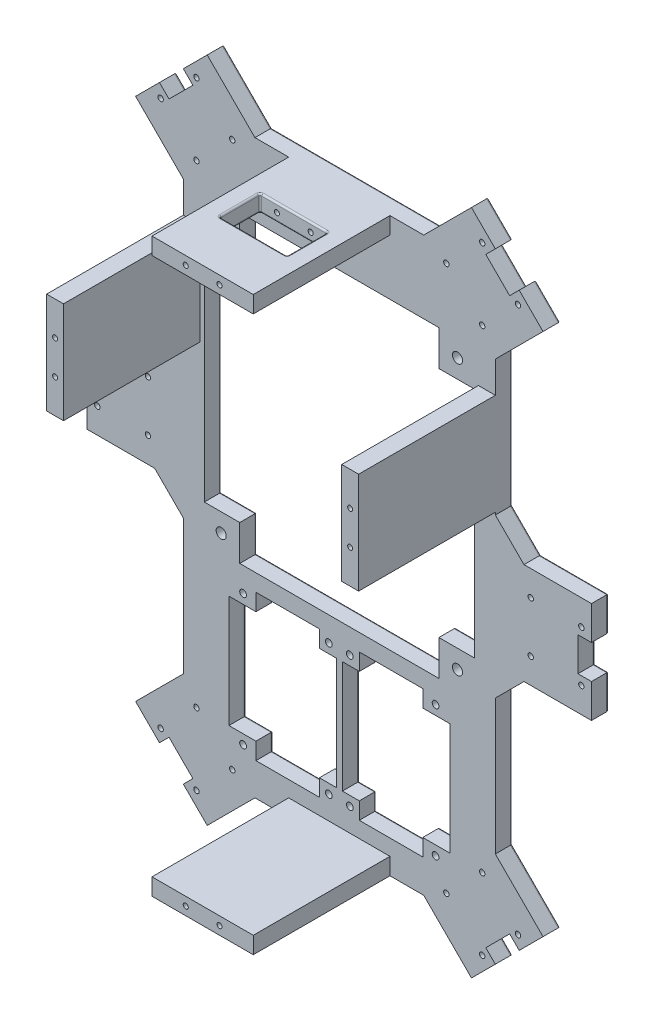
SolidWorks part; units mm, degrees
ref_plane "Płaszczyzna przednia" through (0, 0, 0) normal (0, 0, 1) x (1, 0, 0)
ref_plane "Płaszczyzna górna" through (0, 0, 0) normal (0, 1, 0) x (1, 0, 0)
ref_plane "Płaszczyzna prawa" through (0, 0, 0) normal (1, 0, 0) x (0, 0, -1)
sketch "Szkic1" plane through (0, 0, 0) normal (0, 0, 1) x (1, 0, 0)
  line L0 (0, 0) -> (-50, 0)
  line L1 (-50, 0) -> (-64.1421, 14.1421)
  line L2 (-64.1421, 14.1421) -> (-71.2132, 7.0711)
  line L3 (-71.2132, 7.0711) -> (-68.3848, 4.2426)
  line L4 (-68.3848, 4.2426) -> (-75.4558, -2.8284)
  line L5 (-75.4558, -2.8284) -> (-78.2843, 0)
  line L6 (-78.2843, 0) -> (-85.3553, -7.0711)
  line L7 (-85.3553, -7.0711) -> (-71.2132, -21.2132)
  line L8 (-71.2132, -21.2132) -> (-71.2132, -61.2132)
  line L9 (0, 0) -> (14.1421, 14.1421)
  line L10 (14.1421, 14.1421) -> (21.2132, 7.0711)
  line L11 (21.2132, 7.0711) -> (18.3848, 4.2426)
  line L12 (18.3848, 4.2426) -> (25.4558, -2.8284)
  line L13 (25.4558, -2.8284) -> (28.2843, 0)
  line L14 (28.2843, 0) -> (35.3553, -7.0711)
  line L15 (35.3553, -7.0711) -> (21.2132, -21.2132)
  line L16 (21.2132, -21.2132) -> (21.2132, -61.2132)
  line L17 (-71.2132, -61.2132) -> (-79.6985, -69.6985)
  line L18 (-79.6985, -69.6985) -> (-99.6985, -69.6985)
  line L19 (-99.6985, -69.6985) -> (-99.6985, -79.6985)
  line L20 (-99.6985, -79.6985) -> (-95.6985, -79.6985)
  line L21 (-95.6985, -79.6985) -> (-95.6985, -89.6985)
  line L22 (-95.6985, -89.6985) -> (-99.6985, -89.6985)
  line L23 (-99.6985, -89.6985) -> (-99.6985, -99.6985)
  line L24 (-99.6985, -99.6985) -> (-79.6985, -99.6985)
  line L25 (21.2132, -61.2132) -> (29.6985, -69.6985)
  line L26 (29.6985, -69.6985) -> (49.6985, -69.6985)
  line L27 (49.6985, -69.6985) -> (49.6985, -79.6985)
  line L28 (49.6985, -79.6985) -> (45.6985, -79.6985)
  line L29 (45.6985, -79.6985) -> (45.6985, -89.6985)
  line L30 (45.6985, -89.6985) -> (49.6985, -89.6985)
  line L31 (49.6985, -89.6985) -> (49.6985, -99.6985)
  line L32 (49.6985, -99.6985) -> (29.6985, -99.6985)
  line L33 (29.6985, -99.6985) -> (21.2132, -108.1838)
  line L34 (-79.6985, -99.6985) -> (-71.2132, -108.1838)
  line L35 (-71.2132, -108.1838) -> (-71.2132, -148.1838)
  line L36 (21.2132, -108.1838) -> (21.2132, -148.1838)
  line L37 (-71.2132, -148.1838) -> (-85.3553, -162.3259)
  line L38 (-85.3553, -162.3259) -> (-78.2843, -169.397)
  line L39 (-78.2843, -169.397) -> (-75.4558, -166.5685)
  line L40 (-75.4558, -166.5685) -> (-68.3848, -173.6396)
  line L41 (-68.3848, -173.6396) -> (-71.2132, -176.468)
  line L42 (-71.2132, -176.468) -> (-64.1421, -183.5391)
  line L43 (-64.1421, -183.5391) -> (-50, -169.397)
  line L44 (21.2132, -148.1838) -> (35.3553, -162.3259)
  line L45 (35.3553, -162.3259) -> (28.2843, -169.397)
  line L46 (28.2843, -169.397) -> (25.4558, -166.5685)
  line L47 (25.4558, -166.5685) -> (18.3848, -173.6396)
  line L48 (18.3848, -173.6396) -> (21.2132, -176.468)
  line L49 (21.2132, -176.468) -> (14.1421, -183.5391)
  line L50 (14.1421, -183.5391) -> (0, -169.397)
  line L51 (-50, -169.397) -> (0, -169.397)
  dimension "D1" = 225
  dimension "D2" = 225
  dimension "D3" = 20
  dimension "D4" = 20
  dimension "D5" = 10
  dimension "D6" = 4
  dimension "D7" = 50
  dimension "D8" = 10
  dimension "D9" = 10
  dimension "D10" = 20
  dimension "D11" = 4
  dimension "D12" = 10
  dimension "D13" = 4
  dimension "D14" = 10
  dimension "D15" = 4
  dimension "D16" = 10
  dimension "D17" = 20
  dimension "D18" = 225
  dimension "D19" = 40
  dimension "D20" = 12
  dimension "D21" = 20
  dimension "D22" = 10
  dimension "D23" = 4
  dimension "D24" = 10
  dimension "D25" = 4
  dimension "D26" = 10
  dimension "D27" = 20
  dimension "D29" = 12
  dimension "D30" = 20
  dimension "D31" = 10
  dimension "D32" = 4
  dimension "D33" = 10
  dimension "D34" = 4
  dimension "D35" = 10
  dimension "D36" = 20
  dimension "D37" = 12
  dimension "D38" = 12
  dimension "D39" = 40
  dimension "D40" = 40
  dimension "D41" = 20
  dimension "D42" = 10
  dimension "D43" = 4
  dimension "D44" = 10
  dimension "D45" = 4
  dimension "D46" = 10
  dimension "D47" = 20
  dimension "D48" = 20
  dimension "D49" = 10
  dimension "2" = 4
  dimension "D51" = 10
  dimension "D52" = 4
  dimension "D53" = 10
  dimension "D54" = 20
  dimension "D55" = 135
  dimension "D56" = 90
  dimension "D57" = 270
  dimension "D58" = 225
  dimension "D59" = 225
  dimension "D60" = 135
extrude "Dodanie-wyciągnięcie1" add sketch "Szkic1" along normal blind 5 contours L36 L44 L45 L46 L47 L48 L49 L50 L51 L43 L42 L41 L40 L39 L38 L37 L35 L34 L24 L23 L22 L21 L20 L19 L18 L17 L8 L7 L6 L5 L4 L3 L2 L1 L0 L9 L10 L11 L12 L13 L14 L15 L16 L25 L26 L27 L28 L29 L30 L31 L32 L33
sketch "Szkic3" plane through (0, 0, 0) normal (0, 0, 1) x (1, 0, 0)
  line L0 (49.6985, -69.6985) -> (49.6985, -79.6985) construction
  line L1 (29.6985, -69.6985) -> (49.6985, -69.6985) construction
  line L2 (35.3553, -162.3259) -> (28.2843, -169.397) construction
  line L3 (21.2132, -148.1838) -> (35.3553, -162.3259) construction
  line L4 (21.2132, -176.468) -> (14.1421, -183.5391) construction
  line L5 (14.1421, -183.5391) -> (0, -169.397) construction
  line L6 (-71.2132, -176.468) -> (-64.1421, -183.5391) construction
  line L7 (-85.3553, -162.3259) -> (-78.2843, -169.397) construction
  line L8 (-71.2132, -148.1838) -> (-85.3553, -162.3259) construction
  line L9 (-64.1421, -183.5391) -> (-50, -169.397) construction
  line L10 (35.3553, -7.0711) -> (21.2132, -21.2132) construction
  line L11 (28.2843, 0) -> (35.3553, -7.0711) construction
  line L12 (14.1421, 14.1421) -> (21.2132, 7.0711) construction
  line L13 (0, 0) -> (14.1421, 14.1421) construction
  line L14 (-85.3553, -7.0711) -> (-71.2132, -21.2132) construction
  line L15 (-50, 0) -> (-64.1421, 14.1421) construction
  line L16 (-78.2843, 0) -> (-85.3553, -7.0711) construction
  line L17 (-64.1421, 14.1421) -> (-71.2132, 7.0711) construction
  line L18 (49.6985, -99.6985) -> (29.6985, -99.6985) construction
  line L19 (49.6985, -89.6985) -> (49.6985, -99.6985) construction
  line L20 (-99.6985, -89.6985) -> (-99.6985, -99.6985) construction
  line L21 (-99.6985, -69.6985) -> (-99.6985, -79.6985) construction
  line L22 (-99.6985, -99.6985) -> (-79.6985, -99.6985) construction
  line L23 (-79.6985, -69.6985) -> (-99.6985, -69.6985) construction
  circle A0 centre (31.6985, -77.1985) radius 0.8
  circle A1 centre (46.6985, -77.1985) radius 0.8
  circle A2 centre (31.6985, -92.1985) radius 0.8
  circle A3 centre (46.6985, -92.1985) radius 0.8
  circle A4 centre (-81.6985, -77.1985) radius 0.8
  circle A5 centre (-96.6985, -77.1985) radius 0.8
  circle A6 centre (17.3241, -154.9013) radius 0.8
  circle A7 centre (27.9307, -165.5079) radius 0.8
  circle A8 centre (17.3241, -176.1145) radius 0.8
  circle A9 centre (6.7175, -165.5079) radius 0.8
  circle A10 centre (-67.3241, -154.9013) radius 0.8
  circle A11 centre (-77.9307, -165.5079) radius 0.8
  circle A12 centre (-67.3241, -176.1145) radius 0.8
  circle A13 centre (-56.7175, -165.5079) radius 0.8
  circle A14 centre (17.3241, 6.7175) radius 0.8
  circle A15 centre (27.9307, -3.8891) radius 0.8
  circle A16 centre (6.7175, -3.8891) radius 0.8
  circle A17 centre (17.3241, -14.4957) radius 0.8
  circle A18 centre (-67.3241, 6.7175) radius 0.8
  circle A19 centre (-56.7175, -3.8891) radius 0.8
  circle A20 centre (-77.9307, -3.8891) radius 0.8
  circle A21 centre (-67.3241, -14.4957) radius 0.8
  circle A22 centre (-96.6985, -92.1985) radius 0.8
  circle A23 centre (-81.6985, -92.1985) radius 0.8
  dimension "D1" = 1.6
  dimension "D4" = 1.6
  dimension "D6" = 1.6
  dimension "D7" = 1.6
  dimension "D10" = 1.6
  dimension "D13" = 1.6
  dimension "D16" = 1.6
  dimension "D17" = 1.6
  dimension "D22" = 1.6
  dimension "D23" = 1.6
  dimension "D24" = 1.6
  dimension "D25" = 1.6
  dimension "D34" = 1.6
  dimension "D35" = 1.6
  dimension "D36" = 1.6
  dimension "D37" = 1.6
  dimension "D46" = 1.6
  dimension "D47" = 1.6
  dimension "D48" = 1.6
  dimension "D49" = 1.6
  dimension "D61" = 1.6
  dimension "D62" = 1.6
  dimension "D63" = 1.6
  dimension "D64" = 1.6
  dimension "D2" = 18
  dimension "D3" = 7.5
  dimension "D5" = 15
  dimension "D8" = 15
  dimension "D9" = 15
  dimension "D11" = 18
  dimension "D12" = 7.5
  dimension "D14" = 15
  dimension "D15" = 7.5
  dimension "D18" = 18
  dimension "D19" = 7.5
  dimension "D20" = 7.5
  dimension "D21" = 15
  dimension "D26" = 15
  dimension "D27" = 15
  dimension "D28" = 18
  dimension "D29" = 18
  dimension "D30" = 7.5
  dimension "D31" = 7.5
  dimension "D32" = 7.5
  dimension "D33" = 7.5
  dimension "D38" = 15
  dimension "D39" = 15
  dimension "D40" = 7.5
  dimension "D41" = 7.5
  dimension "D42" = 18
  dimension "D43" = 18
  dimension "D44" = 7.5
  dimension "D45" = 7.5
  dimension "D50" = 7.5
  dimension "D51" = 7.5
  dimension "D52" = 7.5
  dimension "D53" = 7.5
  dimension "D54" = 18
  dimension "D55" = 18
  dimension "D56" = 15
  dimension "D57" = 15
  dimension "D58" = 7.5
  dimension "D59" = 7.5
  dimension "D60" = 18
  dimension "D65" = 18
  dimension "D66" = 18
  dimension "D67" = 15
  dimension "D68" = 15
  dimension "D69" = 7.5
  dimension "D70" = 7.5
  dimension "D71" = 7.5
  dimension "D72" = 7.5
  dimension "D73" = 15
extrude "Wytnij-wyciągnięcie3" cut sketch "Szkic3" against normal blind 4 and the other way blind 16
sketch "Szkic5" plane through (0, 0, 0) normal (0, 0, 1) x (1, 0, 0)
  line L0 (4.4968, -21.5) -> (-54.5032, -21.5)
  line L1 (-54.5032, -21.5) -> (-54.5032, -32)
  line L2 (-54.5032, -32) -> (-65.0032, -32)
  line L3 (-65.0032, -32) -> (-65.0032, -101)
  line L4 (-65.0032, -101) -> (-54.5032, -101)
  line L5 (-54.5032, -101) -> (-54.5032, -111.5)
  line L6 (-54.5032, -111.5) -> (4.4968, -111.5)
  line L7 (4.4968, -111.5) -> (4.4968, -101)
  line L8 (4.4968, -101) -> (14.9968, -101)
  line L9 (14.9968, -101) -> (14.9968, -32)
  line L10 (14.9968, -32) -> (4.4968, -32)
  line L11 (4.4968, -32) -> (4.4968, -21.5)
  line L12 (0, 0) -> (-50, 0) construction
  line L13 (-71.2132, -21.2132) -> (-71.2132, -61.2132) construction
  line L14 (21.2132, -21.2132) -> (21.2132, -61.2132) construction
  line L15 (-71.2132, -21.2132) -> (-71.2132, -61.2132) construction
  circle A0 centre (-60.0032, -26.5) radius 1.5
  circle A1 centre (9.9968, -26.5) radius 1.5
  circle A2 centre (9.9968, -106.5) radius 1.5
  circle A3 centre (-60.0032, -106.5) radius 1.5
  point P14 (-59.7532, -32)
  dimension "D16" = 3
  dimension "D19" = 3
  dimension "D22" = 3
  dimension "D25" = 3
  dimension "D1" = 21.5
  dimension "D2" = 69
  dimension "D3" = 10.5
  dimension "D4" = 10.5
  dimension "D5" = 90
  dimension "D6" = 10.5
  dimension "D7" = 59
  dimension "D8" = 6.21
  dimension "D9" = 10.5
  dimension "D10" = 10.5
  dimension "D11" = 59
  dimension "D12" = 10.5
  dimension "D13" = 10.5
  dimension "D14" = 10.5
  dimension "D15" = 80
  dimension "D17" = 5.5
  dimension "D18" = 5.5
  dimension "D20" = 5.5
  dimension "D21" = 5.5
  dimension "D23" = 5.5
  dimension "D24" = 5.5
  dimension "D26" = 5.5
  dimension "D27" = 5.5
  dimension "D28" = 5
  dimension "D29" = 5
  dimension "D30" = 5
  dimension "D31" = 5
  dimension "D32" = 5
  dimension "D33" = 5
  dimension "D34" = 5
  dimension "D35" = 5
  dimension "D36" = 6.2164
  dimension "D37" = 6.21
  dimension "D38" = 80
  dimension "D39" = 70
  dimension "D40" = 80
  dimension "D41" = 70
  dimension "D42" = 70
extrude "Wytnij-wyciągnięcie4" cut sketch "Szkic5" against normal blind 52 and the other way blind 26
sketch "Szkic6" plane through (0, 0, 5) normal (0, 0, 1) x (1, 0, 0)
  line L0 (-30.9132, -116.497) -> (-49.7132, -116.497)
  line L1 (-49.7132, -116.497) -> (-49.7132, -121.497)
  line L2 (-49.7132, -121.497) -> (-57.7132, -121.497)
  line L3 (-57.7132, -121.497) -> (-57.7132, -154.697)
  line L4 (-57.7132, -154.697) -> (-49.7132, -154.697)
  line L5 (-49.7132, -154.697) -> (-49.7132, -159.697)
  line L6 (-49.7132, -159.697) -> (-30.9132, -159.697)
  line L7 (-30.9132, -159.697) -> (-30.9132, -154.697)
  line L8 (-30.9132, -154.697) -> (-25.9132, -154.697)
  line L9 (-25.9132, -154.697) -> (-25.9132, -121.497)
  line L10 (-25.9132, -121.497) -> (-30.9132, -121.497)
  line L11 (-30.9132, -121.497) -> (-30.9132, -116.497)
  line L12 (-50, -169.397) -> (0, -169.397) construction
  line L13 (-0.2868, -121.497) -> (-0.2868, -116.497)
  line L14 (-71.2132, -108.1838) -> (-71.2132, -148.1838) construction
  line L16 (-19.0868, -116.497) -> (-19.0868, -121.497)
  line L17 (-19.0868, -121.497) -> (-24.0868, -121.497)
  line L18 (-24.0868, -121.497) -> (-24.0868, -154.697)
  line L19 (-24.0868, -154.697) -> (-19.0868, -154.697)
  line L20 (-19.0868, -154.697) -> (-19.0868, -159.697)
  line L21 (-19.0868, -159.697) -> (-0.2868, -159.697)
  line L22 (-0.2868, -159.697) -> (-0.2868, -154.697)
  line L23 (-0.2868, -154.697) -> (7.7132, -154.697)
  line L24 (7.7132, -154.697) -> (7.7132, -121.497)
  line L25 (7.7132, -121.497) -> (-0.2868, -121.497)
  line L26 (-19.0868, -116.497) -> (-0.2868, -116.497)
  line L27 (21.2132, -108.1838) -> (21.2132, -148.1838) construction
  line L28 (4.4968, -111.5) -> (-54.5032, -111.5) construction
  dimension "D1" = 43.2
  dimension "D2" = 9.7
  dimension "D3" = 5
  dimension "D4" = 8
  dimension "D5" = 18.8
  dimension "D6" = 8
  dimension "D7" = 5
  dimension "D8" = 5
  dimension "D9" = 5
  dimension "D10" = 5
  dimension "D11" = 13.5
  dimension "D12" = 33.2
  dimension "D13" = 9.7
  dimension "D14" = 43.2
  dimension "D15" = 5
  dimension "D16" = 33.2
  dimension "D17" = 8
  dimension "D18" = 8
  dimension "D19" = 18.8
  dimension "D20" = 5
  dimension "D21" = 5
  dimension "D22" = 5
  dimension "D23" = 5
  dimension "D24" = 13.5
  dimension "D25" = 1.8264
  dimension "D26" = 4.997
  dimension "D27" = 31.8
  dimension "D28" = 31.8
extrude "Wytnij-wyciągnięcie5" cut sketch "Szkic6" against normal blind 69 and the other way blind 31
sketch "Szkic7" plane through (0, 0, 5) normal (0, 0, 1) x (1, 0, 0)
  line L0 (-49.7132, -121.497) -> (-49.7132, -116.497) construction
  line L1 (-57.7132, -121.497) -> (-49.7132, -121.497) construction
  line L2 (-30.9132, -116.497) -> (-30.9132, -121.497) construction
  line L3 (-30.9132, -121.497) -> (-25.9132, -121.497) construction
  line L4 (-24.0868, -121.497) -> (-19.0868, -121.497) construction
  line L5 (-19.0868, -121.497) -> (-19.0868, -116.497) construction
  line L6 (-0.2868, -121.497) -> (7.7132, -121.497) construction
  line L7 (-0.2868, -116.497) -> (-0.2868, -121.497) construction
  line L8 (7.7132, -154.697) -> (-0.2868, -154.697) construction
  line L9 (-0.2868, -154.697) -> (-0.2868, -159.697) construction
  line L10 (-19.0868, -159.697) -> (-19.0868, -154.697) construction
  line L11 (-19.0868, -154.697) -> (-24.0868, -154.697) construction
  line L12 (-25.9132, -154.697) -> (-30.9132, -154.697) construction
  line L13 (-30.9132, -154.697) -> (-30.9132, -159.697) construction
  line L14 (-49.7132, -159.697) -> (-49.7132, -154.697) construction
  line L15 (-49.7132, -154.697) -> (-57.7132, -154.697) construction
  line L16 (-57.7132, -121.497) -> (-57.7132, -154.697) construction
  line L18 (-49.7132, -159.697) -> (-30.9132, -159.697) construction
  line L19 (-25.9132, -121.497) -> (-25.9132, -154.697) construction
  line L20 (-30.9132, -116.497) -> (-49.7132, -116.497) construction
  line L21 (-19.0868, -116.497) -> (-0.2868, -116.497) construction
  line L22 (-24.0868, -121.497) -> (-24.0868, -154.697) construction
  line L23 (7.7132, -121.497) -> (7.7132, -154.697) construction
  line L24 (-0.2868, -159.697) -> (-19.0868, -159.697) construction
  line L25 (7.7132, -154.697) -> (7.7132, -121.497) construction
  line L26 (-30.9132, -159.697) -> (-49.7132, -159.697) construction
  line L27 (-25.9132, -154.697) -> (-25.9132, -121.497) construction
  circle A0 centre (-53.5132, -118.697) radius 1
  circle A1 centre (-28.1132, -118.697) radius 1
  circle A2 centre (-21.8868, -118.697) radius 1
  circle A3 centre (3.5132, -118.697) radius 1
  circle A4 centre (3.5132, -157.497) radius 1
  circle A5 centre (-21.8868, -157.497) radius 1
  circle A6 centre (-28.1132, -157.497) radius 1
  circle A7 centre (-53.5132, -157.497) radius 1
  dimension "D1" = 2
  dimension "D4" = 2
  dimension "D5" = 2
  dimension "D10" = 2
  dimension "D13" = 2
  dimension "D16" = 2
  dimension "D17" = 2
  dimension "D22" = 2
  dimension "D2" = 3.8
  dimension "D3" = 2.8
  dimension "D6" = 2.8
  dimension "D7" = 2.8
  dimension "D8" = 2.8
  dimension "D9" = 2.8
  dimension "D11" = 2.8
  dimension "D12" = 3.8
  dimension "D14" = 2.8
  dimension "D15" = 3.8
  dimension "D18" = 2.8
  dimension "D19" = 2.8
  dimension "D20" = 2.8
  dimension "D21" = 2.8
  dimension "D23" = 3.8
  dimension "D24" = 2.8
  dimension "D25" = 4.2
  dimension "D26" = 4.2
  dimension "D27" = 2.2
  dimension "D28" = 2.2
  dimension "D29" = 2.2
  dimension "D30" = 2.2
  dimension "D31" = 2.2
  dimension "D32" = 2.2
  dimension "D33" = 4.2
  dimension "D34" = 2.2
  dimension "D35" = 2.2
  dimension "D36" = 2.2
  dimension "D37" = 4.2
  dimension "D38" = 2.2
  dimension "D39" = 2.2
  dimension "D40" = 2.2
extrude "Wytnij-wyciągnięcie6" cut sketch "Szkic7" against normal blind 83 and the other way blind 22
sketch "Szkic8" plane through (0, 0, 0) normal (0, 0, 1) x (1, 0, 0)
  line L0 (-40, 0) -> (-40, -5)
  line L1 (0, 0) -> (-50, 0) construction
  line L2 (-40, -5) -> (-10, -5)
  line L3 (-10, -5) -> (-10, 0)
  line L4 (-10, 0) -> (-40, 0)
  dimension "D1" = 10
  dimension "D2" = 30
  dimension "D3" = 10
  dimension "D4" = 5
extrude "Dodanie-wyciągnięcie2" add sketch "Szkic8" along normal blind 45.5 contours L2 L3 L4 L0
sketch "Szkic10" plane through (0, 0, 5) normal (0, 0, 1) x (1, 0, 0)
  line L0 (-40, -169.397) -> (-40, -164.397)
  line L1 (-50, -169.397) -> (0, -169.397) construction
  line L2 (-40, -164.397) -> (-10, -164.397)
  line L3 (-10, -164.397) -> (-10, -169.397)
  line L4 (-10, -169.397) -> (-40, -169.397)
  dimension "D1" = 30
  dimension "D2" = 5
  dimension "D3" = 10
  dimension "D4" = 10
extrude "Dodanie-wyciągnięcie3" add sketch "Szkic10" along normal blind 40.5
sketch "Szkic11" plane through (0, 0, 45.5) normal (0, 0, 1) x (1, 0, 0)
  line L0 (-10, 0) -> (-40, 0) construction
  line L2 (-40, -5) -> (-40, 0) construction
  line L3 (-10, -5) -> (-10, 0) construction
  circle A0 centre (-30, -2.5) radius 0.75
  circle A1 centre (-20, -2.5) radius 0.75
  dimension "D1" = 1.5
  dimension "D2" = 1.5
  dimension "D3" = 2.5
  dimension "D4" = 2.5
  dimension "D5" = 10
  dimension "D6" = 10
  dimension "D7" = 10
sketch "Szkic12" plane through (0, 0, 45.5) normal (0, 0, 1) x (1, 0, 0)
  line L0 (-10, -164.397) -> (-40, -164.397) construction
  line L1 (-10, -164.397) -> (-40, -164.397) construction
  line L3 (-40, -164.397) -> (-40, -169.397) construction
  line L4 (-10, -169.397) -> (-10, -164.397) construction
  circle A0 centre (-30, -166.897) radius 0.75
  circle A1 centre (-20, -166.897) radius 0.75
  dimension "D1" = 1.5
  dimension "D2" = 1.5
  dimension "D3" = 2.5
  dimension "D4" = 2.5
  dimension "D5" = 10
  dimension "D6" = 10
  dimension "D7" = 10
extrude "Wytnij-wyciągnięcie7" cut sketch "Szkic11" against normal blind 158 and the other way blind 112
extrude "Wytnij-wyciągnięcie8" cut sketch "Szkic12" against normal blind 402 and the other way blind 220
sketch "Szkic13" plane through (0, 0, 5) normal (0, 0, 1) x (1, 0, 0)
  line L0 (-71.2132, -30.5) -> (-66.2132, -30.5)
  line L1 (-71.2132, -21.2132) -> (-71.2132, -61.2132) construction
  line L2 (-66.2132, -30.5) -> (-66.2132, -60.5)
  line L3 (-66.2132, -60.5) -> (-71.2132, -60.5)
  line L4 (-71.2132, -60.5) -> (-71.2132, -30.5)
  line L5 (-65.0032, -32) -> (-54.5032, -32) construction
  line L6 (21.2132, -30.5) -> (16.2132, -30.5)
  line L7 (21.2132, -21.2132) -> (21.2132, -61.2132) construction
  line L8 (16.2132, -30.5) -> (16.2132, -60.5)
  line L9 (16.2132, -60.5) -> (21.2132, -60.5)
  line L10 (21.2132, -60.5) -> (21.2132, -30.5)
  line L11 (4.4968, -32) -> (14.9968, -32) construction
  dimension "D1" = 5
  dimension "D2" = 30
  dimension "D3" = 1.5
  dimension "D4" = 5
  dimension "D5" = 1.5
  dimension "D6" = 30
  dimension "D7" = 5
extrude "Dodanie-wyciągnięcie4" add sketch "Szkic13" along normal blind 40.5
sketch "Szkic14" plane through (0, 0, 0) normal (0, 0, 1) x (1, 0, 0)
  line L0 (-66.2132, -60.5) -> (-66.2132, -30.5) construction
  line L3 (16.2132, -30.5) -> (16.2132, -60.5) construction
  line L4 (16.2132, -30.5) -> (16.2132, -60.5) construction
  line L5 (0, 0) -> (-50, 0) construction
  circle A0 centre (-68.7132, -40.5) radius 0.75
  circle A1 centre (-68.7132, -50.5) radius 0.75
  circle A2 centre (18.7132, -40.5) radius 0.75
  circle A3 centre (18.7132, -50.5) radius 0.75
  dimension "D1" = 1.5
  dimension "D2" = 1.5
  dimension "D3" = 1.5
  dimension "D4" = 1.5
  dimension "D5" = 2.5
  dimension "D6" = 40.5
  dimension "D7" = 50.5
  dimension "D8" = 2.5
  dimension "D9" = 40.5
  dimension "D10" = 50.5
  dimension "D11" = 2.5
  dimension "D12" = 2.5
extrude "Wytnij-wyciągnięcie9" cut sketch "Szkic14" against normal blind 85 and the other way blind 48
fillet "Zaokrąglenie1" radius 0.5 132 edges at (-95.8985, -77.1985, 0) (-80.8985, -77.1985, 0) (-95.8985, -92.1985, 0) (-66.5241, -176.1145, 0) (-80.8985, -92.1985, 0) (-27.1132, -118.697, 0) (-20.8868, -118.697, 0) (4.5132, -118.697, 0) (4.5132, -157.497, 0) (-20.8868, -157.497, 0) (-27.1132, -157.497, 0) (-52.5132, -157.497, 0) (-52.5132, -118.697, 0) (-0.2868, -118.997, 0) (3.7132, -121.497, 0) (7.7132, -138.097, 0) (3.7132, -154.697, 0) (-0.2868, -157.197, 0) (-9.6868, -159.697, 0) (-19.0868, -157.197, 0) (-21.5868, -154.697, 0) (-24.0868, -138.097, 0) (-21.5868, -121.497, 0) (-19.0868, -118.997, 0) (-9.6868, -116.497, 0) (32.4985, -77.1985, 0) (-55.9175, -3.8891, 0) (-77.1307, -3.8891, 0) (-66.5241, -14.4957, 0) (-66.5241, -154.9013, 0) (7.5175, -165.5079, 0) (28.7307, -165.5079, 0) (18.1241, -154.9013, 0) (47.4985, -77.1985, 0) (32.4985, -92.1985, 0) (47.4985, -92.1985, 0) (18.1241, -176.1145, 0) (28.7307, -3.8891, 0) (7.5175, -3.8891, 0) (18.1241, -14.4957, 0) (-66.5241, 6.7175, 0) (18.1241, 6.7175, 0) (-55.9175, -165.5079, 0) (-77.1307, -165.5079, 0) (9.7468, -32, 0) (14.9968, -66.5, 0) (9.7468, -101, 0) (4.4968, -106.25, 0) (-25.0032, -111.5, 0) (-54.5032, -106.25, 0) (-59.7532, -101, 0) (-65.0032, -66.5, 0) (-59.7532, -32, 0) (-54.5032, -26.75, 0) (-25.0032, -21.5, 0) (4.4968, -26.75, 0) (-58.5032, -26.5, 0) (11.4968, -26.5, 0) (11.4968, -106.5, 0) (-58.5032, -106.5, 0) (-28.4132, -121.497, 0) (-25.9132, -138.097, 0) (-28.4132, -154.697, 0) (-30.9132, -157.197, 0) (-40.3132, -159.697, 0) (-49.7132, -157.197, 0) (-53.7132, -154.697, 0) (-57.7132, -138.097, 0) (-53.7132, -121.497, 0) (-49.7132, -118.997, 0) (-40.3132, -116.497, 0) (-30.9132, -118.997, 0) (-67.6777, 10.6066, 0) (-69.799, 5.6569, 0) (-71.9203, 0.7071, 0) (-76.8701, -1.4142, 0) (-81.8198, -3.5355, 0) (-78.2843, -14.1421, 0) (-71.2132, -41.2132, 0) (-75.4558, -65.4558, 0) (-89.6985, -69.6985, 0) (-99.6985, -74.6985, 0) (-97.6985, -79.6985, 0) (-95.6985, -84.6985, 0) (-97.6985, -89.6985, 0) (-99.6985, -94.6985, 0) (-89.6985, -99.6985, 0) (-75.4558, -103.9411, 0) (-71.2132, -128.1838, 0) (-78.2843, -155.2548, 0) (-81.8198, -165.8614, 0) (-76.8701, -167.9828, 0) (-71.9203, -170.1041, 0) (-69.799, -175.0538, 0) (-67.6777, -180.0036, 0) (-57.0711, -176.468, 0) (-25, -169.397, 0) (7.0711, -176.468, 0) (17.6777, -180.0036, 0) (19.799, -175.0538, 0) (21.9203, -170.1041, 0) (26.8701, -167.9828, 0) (31.8198, -165.8614, 0) (28.2843, -155.2548, 0) (21.2132, -128.1838, 0) (25.4558, -103.9411, 0) (39.6985, -99.6985, 0) (49.6985, -94.6985, 0) (47.6985, -89.6985, 0) (45.6985, -84.6985, 0) (47.6985, -79.6985, 0) (49.6985, -74.6985, 0) (39.6985, -69.6985, 0) (25.4558, -65.4558, 0) (21.2132, -41.2132, 0) (28.2843, -14.1421, 0) (31.8198, -3.5355, 0) (26.8701, -1.4142, 0) (21.9203, 0.7071, 0) (19.799, 5.6569, 0) (17.6777, 10.6066, 0) (7.0711, 7.0711, 0) (-25, 0, 0) (-57.0711, 7.0711, 0) (-19.25, -2.5, 0) (-29.25, -2.5, 0) (-19.25, -166.897, 0) (-29.25, -166.897, 0) (-67.9632, -40.5, 0) (19.4632, -50.5, 0) (19.4632, -40.5, 0) (-67.9632, -50.5, 0)
sketch "Szkic15" plane through (0, 0, 0) normal (0, 1, 0) x (1, 0, 0)
  line L0 (-35, -18.5) -> (-35, -30.5)
  line L1 (-35, -30.5) -> (-15, -30.5)
  line L2 (-15, -30.5) -> (-15, -18.5)
  line L3 (-15, -18.5) -> (-35, -18.5)
  line L4 (-40, -45.5) -> (-40, -5) construction
  line L5 (-10, -45.5) -> (-10, -5) construction
  line L6 (-10, -45.5) -> (-40, -45.5) construction
  dimension "D1" = 20
  dimension "D2" = 5
  dimension "D3" = 5
  dimension "D4" = 12
  dimension "D5" = 15
extrude "Wytnij-wyciągnięcie10" cut sketch "Szkic15" against normal blind 21 and the other way blind 19
fillet "Zaokrąglenie2" radius 0.5 12 edges at (-25, -5, 18.5) (-25, -5, 30.5) (-15, -2.5, 30.5) (-15, -5, 24.5) (-15, -2.5, 18.5) (-15, 0, 24.5) (-35, -2.5, 18.5) (-35, -5, 24.5) (-35, -2.5, 30.5) (-35, 0, 24.5) (-25, 0, 18.5) (-25, 0, 30.5)
